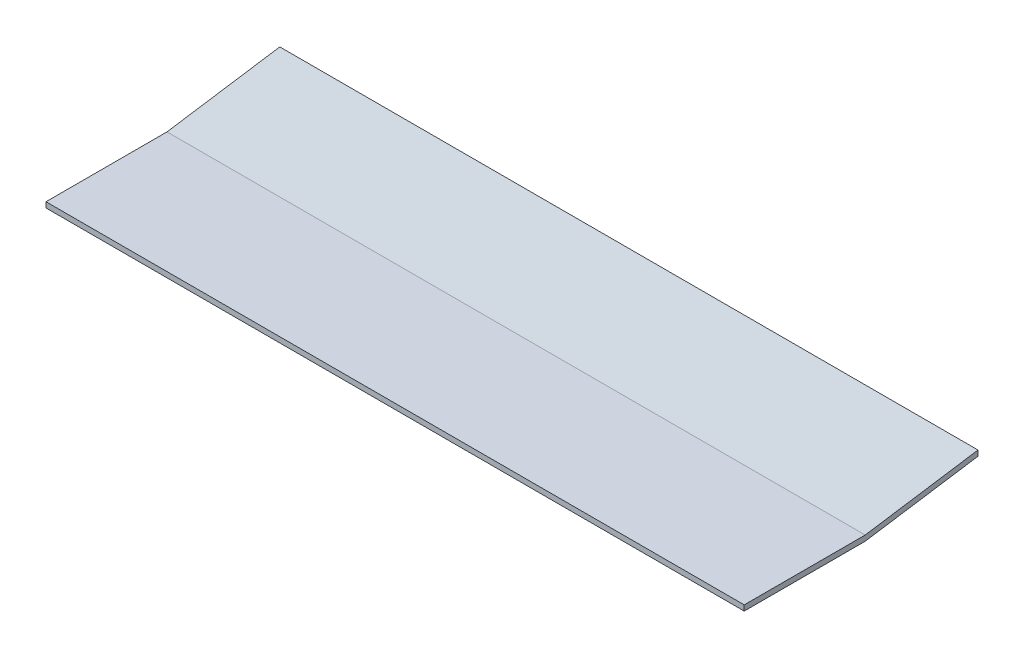
SolidWorks part; units mm, degrees
ref_plane "Спереди" through (0, 0, 0) normal (0, 0, 1) x (1, 0, 0)
ref_plane "Сверху" through (0, 0, 0) normal (0, 1, 0) x (1, 0, 0)
ref_plane "Справа" through (0, 0, 0) normal (1, 0, 0) x (0, 0, -1)
sketch "Эскиз1" plane through (0, 0, 0) normal (1, 0, 0) x (0, 0, -1)
  line L0 (66.39, 15.4305) -> (-930.1738, -136.6492)
  line L1 (-930.1738, -136.6492) -> (-1999.3941, -136.6492)
  line L2 (-1999.3941, -136.6492) -> (-1999.3941, -184.5963)
  line L3 (-1999.3941, -184.5963) -> (-930.1738, -184.5963)
  line L4 (-930.1738, -184.5963) -> (66.39, -32.5166)
  line L5 (66.39, -32.5166) -> (66.39, 15.4305)
extrude "Бобышка-Вытянуть1" add sketch "Эскиз1" along normal blind 6170
